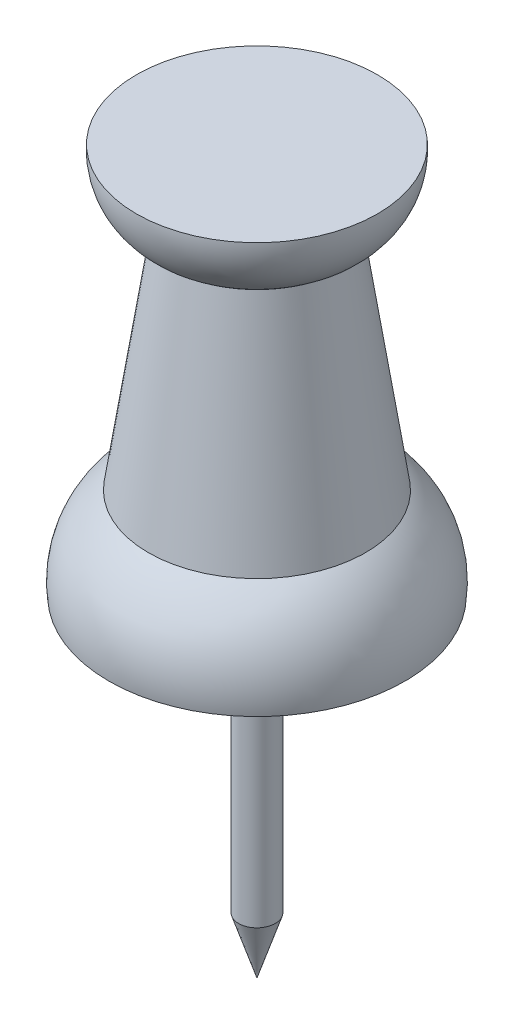
SolidWorks part; units mm, degrees
ref_plane "Front Plane" through (0, 0, 0) normal (0, 0, 1) x (1, 0, 0)
ref_plane "Top Plane" through (0, 0, 0) normal (0, 1, 0) x (1, 0, 0)
ref_plane "Right Plane" through (0, 0, 0) normal (1, 0, 0) x (0, 0, -1)
sketch "Sketch1" plane through (0, 0, 0) normal (0, 0, 1) x (1, 0, 0)
  line L0 (0, 7.0954) -> (0, -18.0756) construction
  line L1 (0, 7.0954) -> (3.95, 7.0954)
  line L2 (2.4383, 4.7954) -> (3.5577, -2.7145)
  line L3 (4.85, -5.7145) -> (0.6, -5.7145)
  line L4 (0.6, -5.7145) -> (0.6, -14.7145)
  line L5 (0.6, -14.7145) -> (0, -16.5611)
  line L6 (0, 7.0954) -> (0, -16.5611)
  arc A0 (3.95, 7.0954) -> (2.4383, 4.7954) centre (1.6541, 6.9576) cw
  arc A1 (3.5577, -2.7145) -> (4.85, -5.7145) centre (1.6765, -5.3032) cw
  dimension "D2" = 2.3
  dimension "D6" = 3
  dimension "D7" = 3.2
  dimension "D1" = 3.95
  dimension "D3" = 2.3
  dimension "D4" = 7.5099
  dimension "D8" = 18
  dimension "D9" = 9
revolve "Revolve1" add sketch "Sketch1" angle 360 about L0
